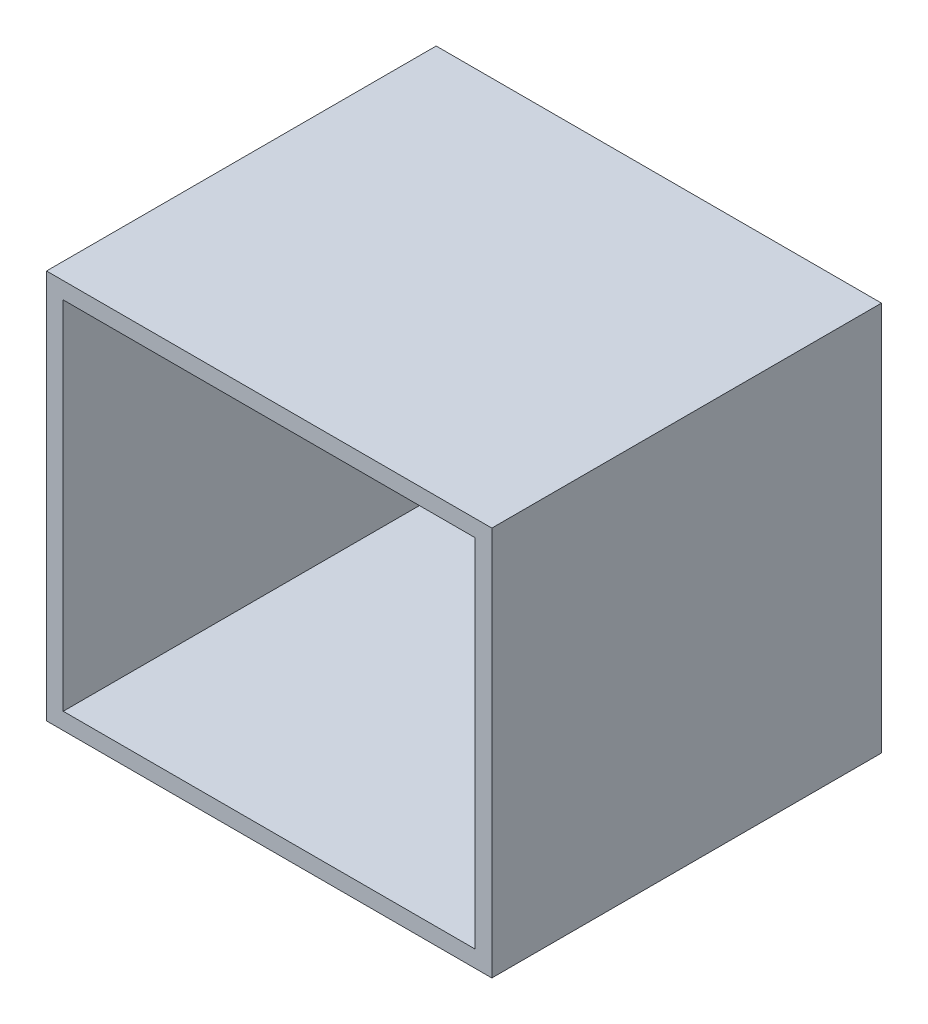
SolidWorks part; units mm, degrees
ref_plane "Front Plane" through (0, 0, 0) normal (0, 0, 1) x (1, 0, 0)
ref_plane "Top Plane" through (0, 0, 0) normal (0, 1, 0) x (1, 0, 0)
ref_plane "Right Plane" through (0, 0, 0) normal (1, 0, 0) x (0, 0, -1)
sketch "Sketch1" plane through (0, 0, 0) normal (0, 0, 1) x (1, 0, 0)
  line L0 (385, -42.1449) -> (400, -42.1449) construction
  line L6 (0, -175) -> (400, -175)
  line L7 (0, -175) -> (0, 175)
  line L11 (0, 175) -> (400, 175)
  line L12 (400, -175) -> (400, 175)
  line L13 (15, 160) -> (385, 160)
  line L14 (15, 160) -> (15, -160)
  line L15 (15, -160) -> (385, -160)
  line L16 (385, 160) -> (385, -160)
  line L17 (259.0988, -160) -> (259.0988, -175) construction
  line L18 (15, -61.7741) -> (0, -61.7741) construction
  line L19 (148.1047, 160) -> (148.1047, 175) construction
  point P0 (0, 0)
  point P7 (0, 0)
  dimension "D1" = 400
  dimension "D2" = 350
  dimension "D3" = 15
extrude "Boss-Extrude1" add sketch "Sketch1" along normal blind 350
